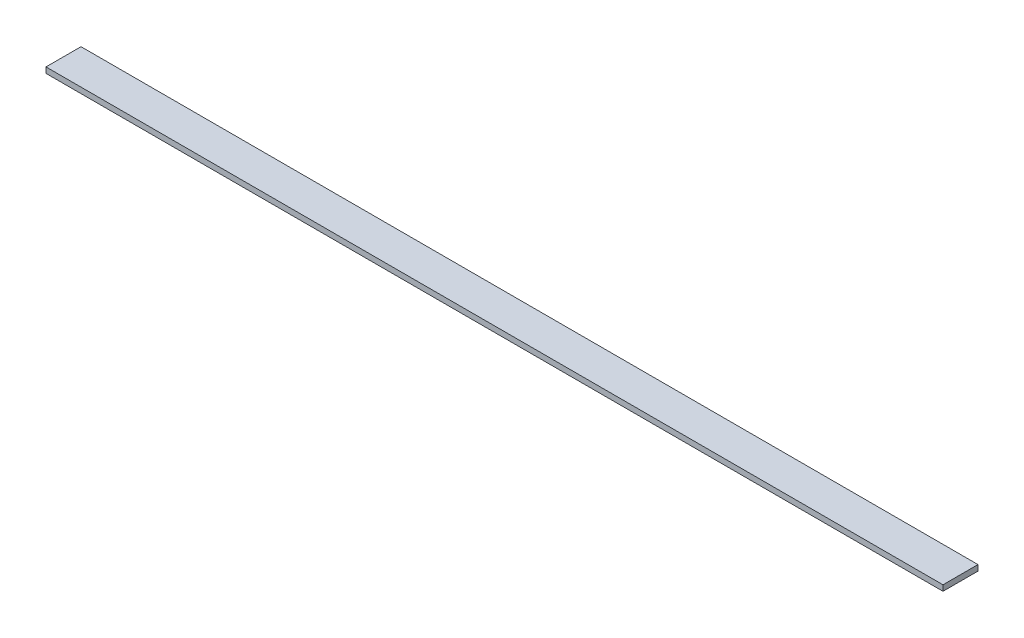
SolidWorks part; units mm, degrees
material "Pine"
ref_plane "Front Plane" through (0, 0, 0) normal (0, 0, 1) x (1, 0, 0)
ref_plane "Top Plane" through (0, 0, 0) normal (0, 1, 0) x (1, 0, 0)
ref_plane "Right Plane" through (0, 0, 0) normal (1, 0, 0) x (0, 0, -1)
sketch "Sketch3" plane through (0, 0, 0) normal (0, 1, 0) x (1, 0, 0)
  line L1 (-3811.4111, 1664.2292) -> (2208.3889, 1664.2292)
  line L2 (-3811.4111, 1664.2292) -> (-3811.4111, 1429.2792)
  line L3 (-3811.4111, 1429.2792) -> (2208.3889, 1429.2792)
  line L4 (2208.3889, 1664.2292) -> (2208.3889, 1429.2792)
  dimension "D1" = 234.95
  dimension "D2" = 6019.8
extrude "Boss-Extrude1" add sketch "Sketch3" along normal blind 38.1
